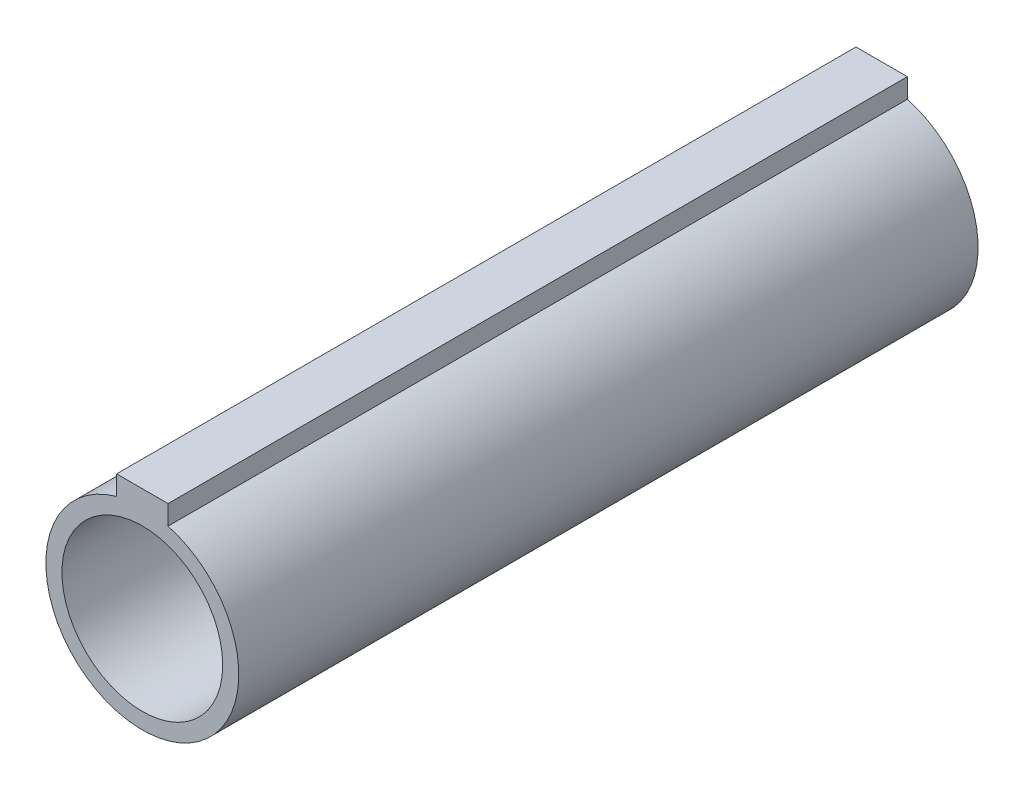
SolidWorks part; units mm, degrees
ref_plane "Front Plane" through (0, 0, 0) normal (0, 0, 1) x (1, 0, 0)
ref_plane "Top Plane" through (0, 0, 0) normal (0, 1, 0) x (1, 0, 0)
ref_plane "Right Plane" through (0, 0, 0) normal (1, 0, 0) x (0, 0, -1)
sketch "Sketch1" plane through (0, 0, 0) normal (0, 0, 1) x (1, 0, 0)
  circle A0 centre (0, 0) radius 15
  circle A1 centre (0, 0) radius 12.5
  dimension "D1" = 30
  dimension "D2" = 25
extrude "Boss-Extrude1" add sketch "Sketch1" along normal blind 115 contours A0 A1
sketch "Sketch2" plane through (0, 0, 0) normal (0, 0, 1) x (1, 0, 0)
  line L0 (0, -23.8145) -> (0, 33.6553) construction
  line L2 (4, 17.5) -> (-4, 17.5)
  line L3 (4, 17.5) -> (4, 12.5)
  line L4 (4, 12.5) -> (-4, 12.5)
  line L5 (-4, 17.5) -> (-4, 12.5)
  line L6 (4, 17.5) -> (-4, 12.5) construction
  line L7 (4, 12.5) -> (-4, 17.5) construction
  point P3 (0, 15)
  point P4 (0, 15)
  dimension "D1" = 15
  dimension "D2" = 8
  dimension "D3" = 5
extrude "Boss-Extrude2" add sketch "Sketch2" along normal blind 115
